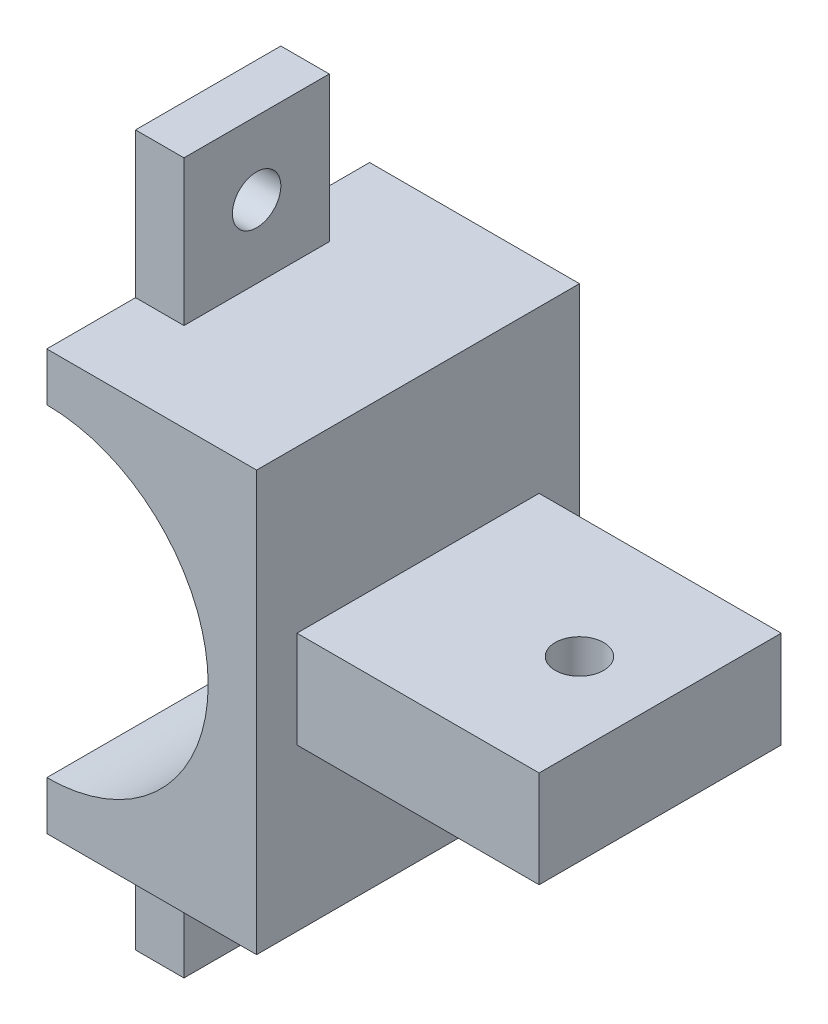
SolidWorks part; units mm, degrees
ref_plane "Спереди" through (0, 0, 0) normal (0, 0, 1) x (1, 0, 0)
ref_plane "Сверху" through (0, 0, 0) normal (0, 1, 0) x (1, 0, 0)
ref_plane "Справа" through (0, 0, 0) normal (1, 0, 0) x (0, 0, -1)
sketch "Эскиз1" plane through (0, 0, 0) normal (0, 0, 1) x (1, 0, 0)
  line L0 (0, 10) -> (0, 13)
  line L1 (0, -10) -> (0, -13)
  line L2 (0, 0) -> (10, 0) construction
  line L3 (0, 0) -> (0, -10) construction
  line L4 (0, 13) -> (13, 13)
  line L5 (10, 0) -> (55, 0) construction
  line L6 (13, 13) -> (13, -13)
  line L7 (13, -13) -> (0, -13)
  arc A0 (0, 10) -> (0, -10) centre (0, 0) cw
  point P9 (0, 0)
  dimension "D1" = 10
  dimension "D4" = 13
  dimension "D2" = 3
  dimension "D3" = 20
  dimension "D5" = 3
extrude "Бобышка-Вытянуть1" add sketch "Эскиз1" along normal blind 20
sketch "Эскиз7" plane through (0, 0, 0) normal (-1, 0, 0) x (0, 0, 1)
  line L1 (20, 10) -> (0, 10) construction
  line L2 (5.5, 10) -> (5.5, 22)
  line L3 (5.5, 22) -> (14.5, 22)
  line L4 (14.5, 22) -> (14.5, 10)
  line L6 (5.5, 10) -> (14.5, 10)
  line L7 (10, 10) -> (10, 17.5) construction
  line L8 (10, -10) -> (10, -17.5) construction
  line L10 (20, -10) -> (0, -10) construction
  line L11 (14.5, -10) -> (5.5, -10)
  line L12 (5.5, -10) -> (5.5, -22)
  line L13 (5.5, -22) -> (14.5, -22)
  line L14 (14.5, -22) -> (14.5, -10)
  circle A0 centre (10, 17.5) radius 1.5
  circle A1 centre (10, -17.5) radius 1.5
  dimension "D1" = 3
  dimension "D2" = 12
  dimension "D3" = 7.5
  dimension "D4" = 9
  dimension "D5" = 10
extrude "Бобышка-Вытянуть3" add sketch "Эскиз7" against normal blind 3
sketch "Эскиз8" plane through (13, 0, 0) normal (1, 0, 0) x (0, 0, -1)
  line L0 (0, 0) -> (-20, 0) construction
  line L1 (-20, -13) -> (-20, 13) construction
  line L2 (-10, 0) -> (-10, 3) construction
  line L3 (-10, 0) -> (-10, -3) construction
  line L5 (-17.5, 3) -> (-17.5, -3)
  line L6 (-17.5, -3) -> (-2.5, -3)
  line L7 (-2.5, -3) -> (-2.5, 3)
  line L10 (-17.5, 3) -> (-10, 3)
  line L11 (-10, 3) -> (-2.5, 3)
  dimension "D1" = 15
  dimension "D2" = 6
  dimension "D3" = 3
extrude "Бобышка-Вытянуть4" add sketch "Эскиз8" along normal blind 15
sketch "Эскиз9" plane through (0, 3, 0) normal (0, 1, 0) x (1, 0, 0)
  line L0 (28, -10) -> (23, -10) construction
  line L1 (28, -2.5) -> (28, -17.5) construction
  circle A0 centre (23, -10) radius 1.5
  dimension "D1" = 3
  dimension "D2" = 5
extrude "Вырез-Вытянуть1" cut sketch "Эскиз9" against normal blind 15
sketch "Эскиз6" plane through (0, 0, 0) normal (-1, 0, 0) x (0, 0, 1)
  line L0 (10, 10) -> (10, -10) construction
  line L1 (20, 10) -> (0, 10) construction
  line L2 (20, -10) -> (0, -10) construction
  line L3 (10, 10) -> (5.5, 10)
  line L4 (5.5, 10) -> (5.5, 22)
  line L5 (5.5, 22) -> (14.5, 22)
  line L6 (14.5, 22) -> (14.5, 10)
  line L7 (14.5, 10) -> (10, 10)
  line L8 (10, -10) -> (5.5, -10)
  line L9 (5.5, -10) -> (5.5, -22)
  line L10 (5.5, -22) -> (14.5, -22)
  line L11 (14.5, -22) -> (14.5, -10)
  line L12 (14.5, -10) -> (10, -10)
  circle A0 centre (10, 17.5) radius 1.5
  circle A1 centre (10, -17.5) radius 1.5
  dimension "D1" = 3
  dimension "D6" = 4.5
  dimension "D2" = 4.5
  dimension "D3" = 7.5
  dimension "D4" = 12
  dimension "D5" = 4.5
  dimension "D7" = 7.5
extrude "Бобышка-Вытянуть2" add sketch "Эскиз6" against normal blind 3
